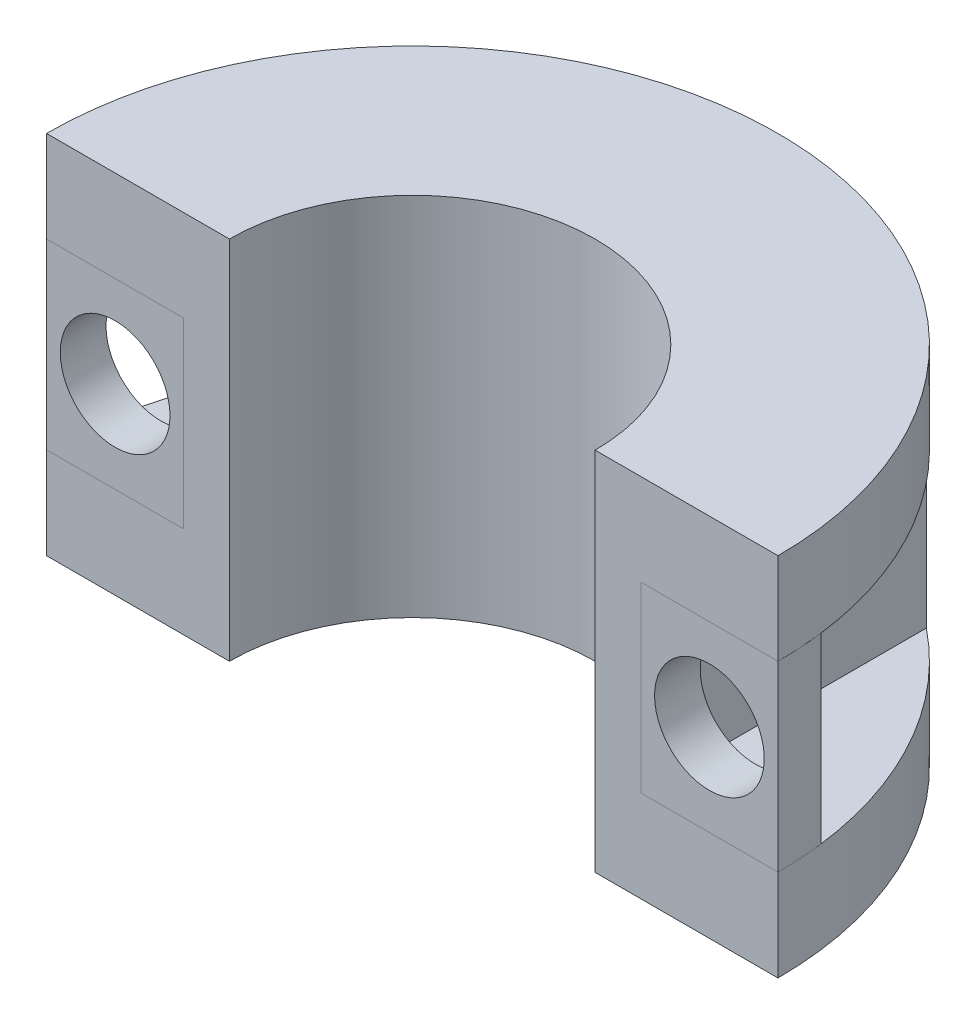
SolidWorks part; units mm, degrees
ref_plane "Front Plane" through (0, 0, 0) normal (0, 0, 1) x (1, 0, 0)
ref_plane "Top Plane" through (0, 0, 0) normal (0, 1, 0) x (1, 0, 0)
ref_plane "Right Plane" through (0, 0, 0) normal (1, 0, 0) x (0, 0, -1)
sketch "Sketch1" plane through (0, 0, 0) normal (0, 1, 0) x (1, 0, 0)
  line L9 (-8, -1.5) -> (-4, -1.5)
  line L10 (4, -1.5) -> (8, -1.5)
  arc A3 (-4, -1.5) -> (4, -1.5) centre (0, -1.5) cw
  arc A4 (-8, -1.5) -> (8, -1.5) centre (0, -1.5) cw
extrude "Boss-Extrude1" add sketch "Sketch1" along normal blind 8
sketch "Sketch2" plane through (0, 0, 1.5) normal (0, 0, 1) x (1, 0, 0)
  line L0 (-8, 4) -> (-8, 6)
  line L1 (-8, 8) -> (-8, 0) construction
  line L2 (-8, 6) -> (-5, 6)
  line L3 (-5, 6) -> (-5, 2.0061)
  line L4 (-5, 2.0061) -> (-8, 2.0061)
  line L5 (-8, 2.0061) -> (-8, 4)
  line L6 (8, 8) -> (8, 0) construction
  line L7 (8, 6) -> (5, 6)
  line L8 (8, 6) -> (8, 2.0061)
  line L9 (8, 2.0061) -> (5, 2.0061)
  line L10 (5, 6) -> (5, 2.0061)
extrude "Cut-Extrude1" cut sketch "Sketch2" against normal blind 10
sketch "Sketch3" plane through (0, 0, 1.5) normal (0, 0, 1) x (1, 0, 0)
  line L1 (-5, 6) -> (-8, 6)
  line L2 (-5, 6) -> (-5, 2.0061)
  line L3 (-5, 2.0061) -> (-8, 2.0061)
  line L4 (-8, 6) -> (-8, 2.0061)
  line L5 (5, 6) -> (8, 6)
  line L6 (5, 6) -> (5, 2.0061)
  line L7 (5, 2.0061) -> (8, 2.0061)
  line L8 (8, 6) -> (8, 2.0061)
extrude "Boss-Extrude2" add sketch "Sketch3" against normal blind 1 separate body
sketch "Sketch4" plane through (0, 0, 0) normal (0, -1, 0) x (1, 0, 0)
  line L0 (-8, 1.5) -> (-8, 0.5)
  line L1 (-8, 0.5) -> (-7.931, 0.5)
  line L3 (8, 1.5) -> (8, 0.5)
  line L4 (8, 0.5) -> (7.9308, 0.5)
  line L6 (5, 0.5) -> (8, 0.5) construction
  arc A1 (-8, 1.5) -> (-7.9373, 0.5) centre (0, 1.5) ccw
  arc A2 (8, 1.5) -> (7.9371, 0.4989) centre (0, 1.5) cw
  arc M3 (-8, 1.5) -> (8, 1.5) centre (0, 1.5) ccw
extrude "Cut-Extrude2" cut sketch "Sketch4" against normal blind 8 contours L0 L1 M3 | L4 L3 M3
sketch "Sketch5" plane through (0, 0, 0.5) normal (0, 0, -1) x (-1, 0, 0)
  line L0 (8, 6) -> (8, 2.0061) construction
  line L1 (-8, 2.0061) -> (-8, 6) construction
  circle A0 centre (8, 4.0031) radius 1.5
  circle A1 centre (6.5, 4.0031) radius 1.2
  circle A2 centre (-8, 4.0031) radius 1.5
  circle A3 centre (-6.5, 4.0031) radius 1.2
extrude "Cut-Extrude3" cut sketch "Sketch5" against normal blind 1 contours A0 A1 | A0 A1 | A2 A3 | A2 A3
